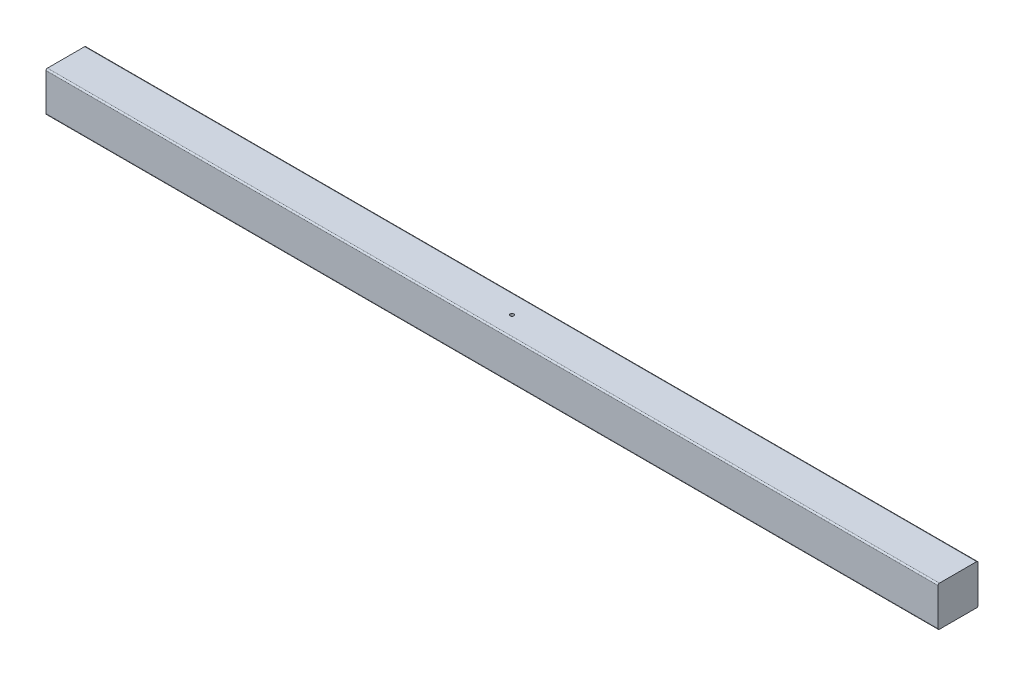
SolidWorks part; units mm, degrees
material "Pine"
ref_plane "Front Plane" through (0, 0, 0) normal (0, 0, 1) x (1, 0, 0)
ref_plane "Top Plane" through (0, 0, 0) normal (0, 1, 0) x (1, 0, 0)
ref_plane "Right Plane" through (0, 0, 0) normal (1, 0, 0) x (0, 0, -1)
sketch "Sketch1" plane through (0, 0, 0) normal (1, 0, 0) x (0, 0, -1)
  line L1 (-44.45, -44.45) -> (44.45, -44.45)
  line L2 (-44.45, -44.45) -> (-44.45, 44.45)
  line L3 (-44.45, 44.45) -> (44.45, 44.45)
  line L4 (44.45, -44.45) -> (44.45, 44.45)
  line L5 (-44.45, -44.45) -> (44.45, 44.45) construction
  line L6 (-44.45, 44.45) -> (44.45, -44.45) construction
  point P0 (0, 0)
  dimension "D1" = 88.9
extrude "Boss-Extrude1" add sketch "Sketch1" along normal blind 1981.2
fillet "Fillet1" radius 3.175 4 edges at (990.6, -44.45, -44.45) (990.6, 44.45, -44.45) (990.6, -44.45, 44.45) (990.6, 44.45, 44.45)
hole_wizard "5/16 (0.3125) Diameter Hole1" positions "Sketch2" profile "Sketch3" hole size "5/16" standard "ANSI Inch" end condition through all
sketch "Sketch2" plane through (0, 44.45, 0) normal (0, 1, 0) x (1, 0, 0)
  line L0 (1981.2, -44.45) -> (0, -44.45) construction
  line L1 (0, 44.45) -> (1981.2, 44.45) construction
  line L2 (1981.2, -44.45) -> (0, -44.45) construction
  line L3 (0, 44.45) -> (1981.2, 44.45) construction
  point P0 (990.6, 0)
  point P10 (990.6, 44.45)
sketch "Sketch3" plane through (990.6, 44.45, 0) normal (1, 0, 0) x (0, 0, 1)
  line L0 (0, 0) -> (0, 88.9)
  line L1 (0, 88.9) -> (3.9687, 88.9)
  line L2 (3.9687, 88.9) -> (3.9687, 0)
  line L5 (3.9687, 0) -> (0, 0)
  line L11 (0, -6.35) -> (0, 107.95) construction
  dimension "Thru Hole Dia." = 7.9375
  dimension "Thru Hole Depth" = 88.9
